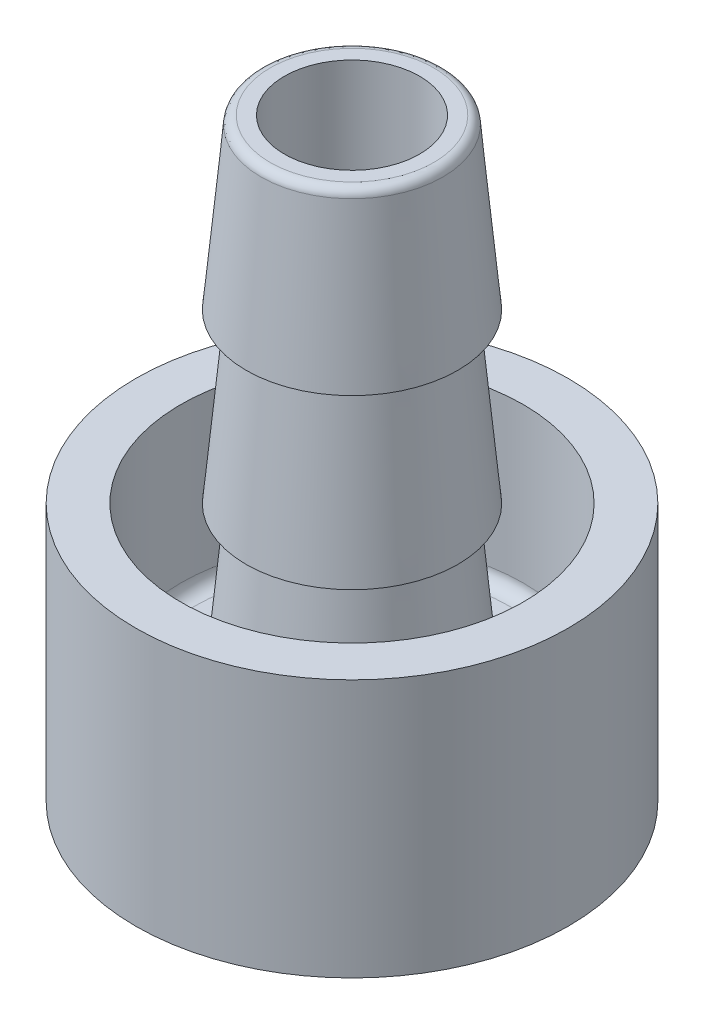
SolidWorks part; units mm, degrees
ref_plane "Alzado" through (0, 0, 0) normal (0, 0, 1) x (1, 0, 0)
ref_plane "Planta" through (0, 0, 0) normal (0, 1, 0) x (1, 0, 0)
ref_plane "Vista lateral" through (0, 0, 0) normal (1, 0, 0) x (0, 0, -1)
sketch "Croquis1" plane through (0, 0, 0) normal (0, 0, 1) x (1, 0, 0)
  line L0 (2.35, 0.01) -> (2.35, 11.2) construction
  line L1 (2, 0) -> (2, 11.2) construction
  line L2 (2, 11.2) -> (2.35, 7.47)
  line L3 (2.35, 7.47) -> (2, 7.47)
  line L4 (2, 7.47) -> (2.35, 3.74)
  line L5 (2.35, 3.74) -> (2, 3.74)
  line L6 (2, 3.74) -> (2.35, 0.01)
  line L7 (1.5, 11.2) -> (1.5, 5.605)
  line L8 (1.5, 11.2) -> (2, 11.2)
  line L9 (2.35, 0.01) -> (3.8, 0.01)
  line L10 (3.8, 0.01) -> (3.8, 3.74)
  line L11 (3.8, 3.74) -> (4.8, 3.74)
  line L12 (4.8, 3.74) -> (4.8, -1.99)
  line L14 (0, 0) -> (0, 11.2) construction
  line L15 (4.8, -1.99) -> (1.3, -1.99)
  line L16 (1.3, -1.99) -> (1.3, 3)
  line L17 (1.3, 3) -> (1.5, 5.605)
  point P5 (0, 0)
  point P20 (2.175, 5.605)
  dimension "D1" = 2.35
  dimension "D2" = 2
  dimension "D3" = 11.2
  dimension "D4" = 3.74
  dimension "D5" = 0.5
  dimension "D6" = 3.8
  dimension "D7" = 1
  dimension "D8" = 1.3
  dimension "D9" = 3
  dimension "D10" = 2
revolve "Revolución1" add sketch "Croquis1" angle 360 about L14
fillet "Redondeo1" radius 0.2 1 edges at (0, 11.2, -2)
sketch "Croquis2" plane through (0, -1.99, 0) normal (0, -1, 0) x (1, 0, 0)
  line L10 (0, 2.05) -> (0, -2.05) construction
  line L11 (2.05, 0) -> (-2.05, 0) construction
  line L12 (2.15, 0.7) -> (2.15, -0.7)
  line L13 (0.7, -2.15) -> (-0.9944, -2.15)
  line L14 (-1.4186, -1.9743) -> (-1.9743, -1.4186)
  line L15 (-2.15, -0.9944) -> (-2.15, 0.7)
  line L16 (-0.7, 2.15) -> (0.7, 2.15)
  arc A5 (0.7, -2.15) -> (2.15, -0.7) centre (0.7, -0.7) ccw
  arc A6 (-1.4186, -1.9743) -> (-0.9944, -2.15) centre (-0.9944, -1.55) ccw
  arc A7 (-2.15, -0.9944) -> (-1.9743, -1.4186) centre (-1.55, -0.9944) ccw
  arc A8 (-0.7, 2.15) -> (-2.15, 0.7) centre (-0.7, 0.7) ccw
  arc A9 (2.15, 0.7) -> (0.7, 2.15) centre (0.7, 0.7) ccw
  point P19 (0, 0)
  point P20 (0, 0)
  dimension "D6" = 4.1
  dimension "D7" = 4.1
extrude "Cortar-Extruir1" cut sketch "Croquis2" against normal blind 1.25
fillet "Redondeo2" radius 0.3 21 edges at (0, -0.74, -1.3) (-2.1043, -0.74, -1.224) (-2.15, -0.74, -0.1472) (-1.7253, -0.74, 1.7253) (0, -0.74, 2.15) (1.7253, -0.74, 1.7253) (2.15, -0.74, 0) (1.7253, -0.74, -1.7253) (-0.1472, -0.74, -2.15) (-1.224, -0.74, -2.1043) (-2.1043, -1.99, -1.224) (-2.15, -1.99, -0.1472) (-1.7253, -1.99, 1.7253) (0, -1.99, 2.15) (1.7253, -1.99, 1.7253) (2.15, -1.99, 0) (1.7253, -1.99, -1.7253) (-0.1472, -1.99, -2.15) (-1.224, -1.99, -2.1043) (-1.6964, -0.74, -1.6964) (-1.6964, -1.99, -1.6964)
fillet "Redondeo3" radius 0.3 1 edges at (0, 0.01, -3.8)
